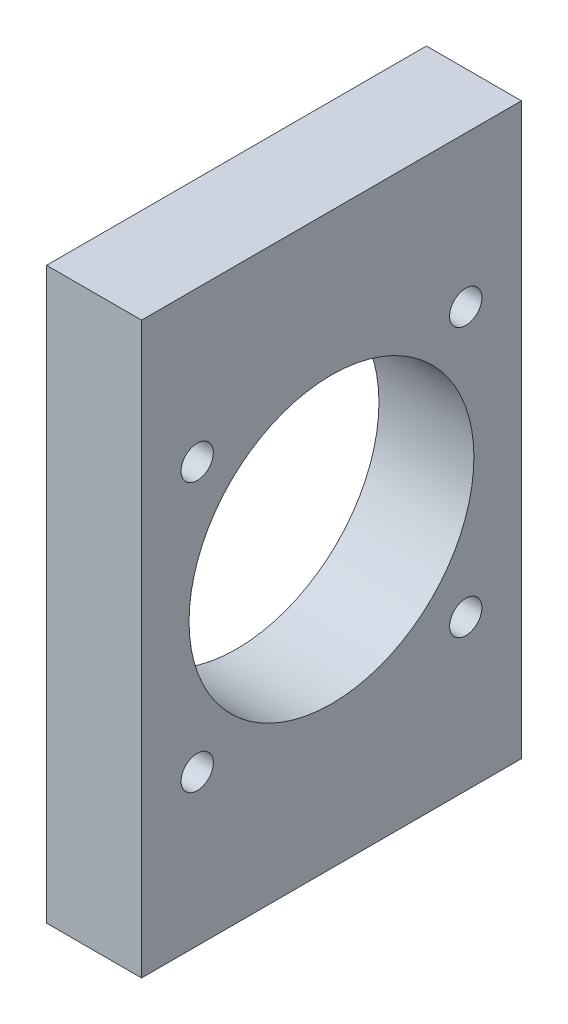
SolidWorks part; units mm, degrees
material "PA Type 6"
ref_plane "Front Plane" through (0, 0, 0) normal (0, 0, 1) x (1, 0, 0)
ref_plane "Top Plane" through (0, 0, 0) normal (0, 1, 0) x (1, 0, 0)
ref_plane "Right Plane" through (0, 0, 0) normal (1, 0, 0) x (0, 0, -1)
sketch "Sketch1" plane through (0, 0, 0) normal (1, 0, 0) x (0, 0, -1)
  line L1 (0, 0) -> (40, 0)
  line L2 (0, 0) -> (0, 60)
  line L3 (0, 60) -> (40, 60)
  line L4 (40, 0) -> (40, 60)
  dimension "D1" = 60
  dimension "D2" = 40
extrude "Boss-Extrude1" add sketch "Sketch1" along normal blind 10
sketch "Sketch2" plane through (0, 0, 0) normal (1, 0, 0) x (0, 0, -1)
  line L0 (20, 0) -> (20, 66.0795) construction
  line L1 (0, 0) -> (40, 0) construction
  line L3 (20, 30) -> (5.8579, 44.1421)
  line L4 (34.1421, 44.1421) -> (5.8579, 44.1421) construction
  circle A0 centre (20, 30) radius 20
  point P10 (5.8579, 44.1421)
  point P22 (34.1421, 44.1421)
  point P23 (34.1421, 15.8579)
  point P24 (5.8579, 15.8579)
  dimension "D1" = 40
  dimension "D2" = 4
  dimension "D3" = 30
hole_wizard "CBORE for M3 Hex Socket Thin Head Cap Screw1" positions "Sketch2" profile "Sketch3" counterbore size "M3" standard "DIN" end condition through all
sketch "Sketch3" plane through (0, 15.8579, -5.8579) normal (0, 1, 0) x (0, 0, 1)
  line L0 (0, 0) -> (0, 10)
  line L1 (0, 10) -> (1.7, 10)
  line L3 (1.7, 10) -> (1.7, 2.4)
  line L4 (1.7, 2.4) -> (3.25, 2.4)
  line L5 (3.25, 2.4) -> (3.25, 0)
  line L7 (3.25, 0) -> (0, 0)
  line L11 (0, -6.35) -> (0, 107.95) construction
  dimension "Thru Hole Dia." = 3.4
  dimension "Thru Hole Depth" = 10
  dimension "C'Bore Dia." = 6.5
  dimension "C'Bore Depth" = 2.4
sketch "Sketch4" plane through (0, 0, 0) normal (-1, 0, 0) x (0, 0, 1)
  circle A0 centre (-20, 30) radius 20 construction
  circle A3 centre (-20, 30) radius 15
  point P3 (-34.1421, 44.1421)
  point P4 (-34.1421, 15.8579)
  dimension "D1" = 30
extrude "Cut-Extrude1" cut sketch "Sketch4" against normal through all
